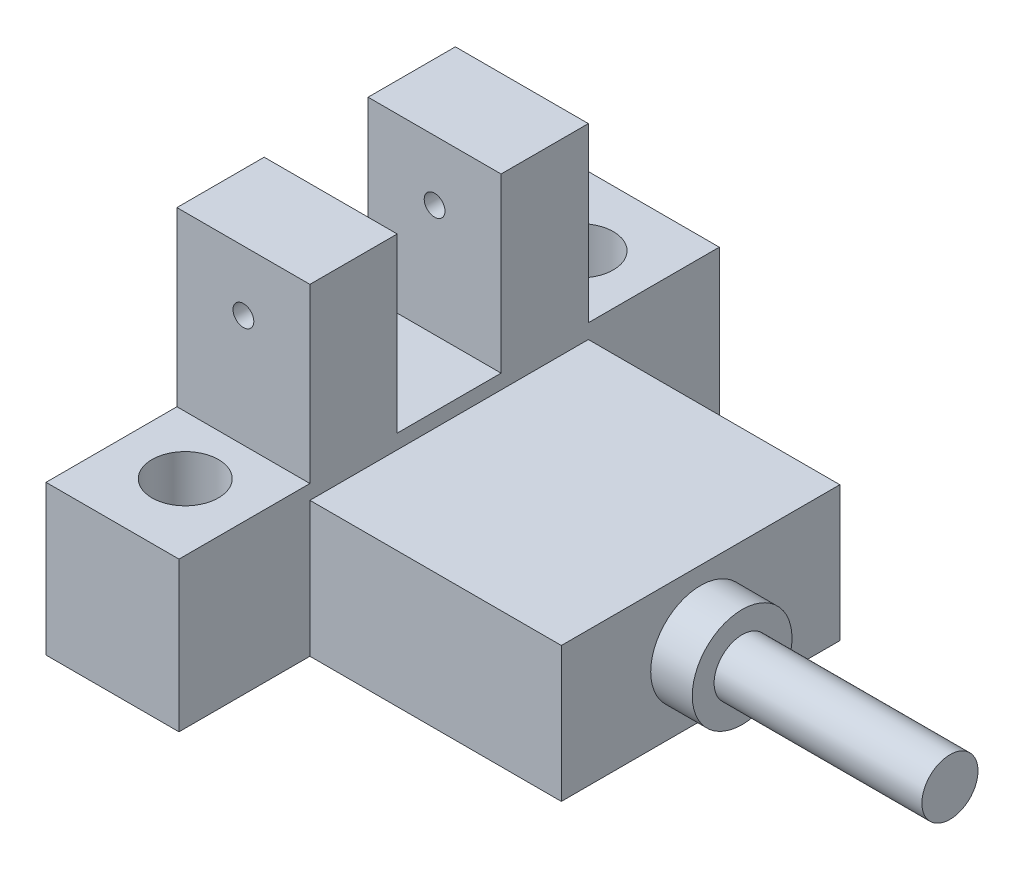
SolidWorks part; units mm, degrees
ref_plane "Ebene vorne" through (0, 0, 0) normal (0, 0, 1) x (1, 0, 0)
ref_plane "Ebene oben" through (0, 0, 0) normal (0, 1, 0) x (1, 0, 0)
ref_plane "Ebene rechts" through (0, 0, 0) normal (1, 0, 0) x (0, 0, -1)
sketch "Skizze1" plane through (0, 0, 0) normal (0, 0, 1) x (1, 0, 0)
  line L0 (0, 0) -> (0, 15.5)
  line L1 (0, 15.5) -> (6.4, 15.5)
  line L2 (6.4, 15.5) -> (6.4, 6.5)
  line L3 (6.4, 6.5) -> (18.5, 6.5)
  line L4 (18.5, 6.5) -> (18.5, 0)
  line L5 (18.5, 0) -> (0, 0)
  dimension "D1" = 6.5
  dimension "D2" = 6.4
  dimension "D3" = 18.5
  dimension "D4" = 15.5
extrude "Aufsatz-Linear austragen1" add sketch "Skizze1" along normal blind 26
sketch "Skizze2" plane through (0, 6.5, 0) normal (0, 1, 0) x (1, 0, 0)
  line L0 (6.4, -26) -> (6.4, 0) construction
  line L1 (6.4, -19.7) -> (18.5, -19.7)
  line L2 (6.4, -19.7) -> (6.4, -26)
  line L3 (6.4, -26) -> (18.5, -26)
  line L4 (18.5, -19.7) -> (18.5, -26)
  line L5 (18.5, -26) -> (18.5, 0) construction
  line L6 (6.4, 0) -> (18.5, 0)
  line L7 (6.4, 0) -> (6.4, -6.3)
  line L8 (6.4, -6.3) -> (18.5, -6.3)
  line L9 (18.5, 0) -> (18.5, -6.3)
  point P14 (18.5, -13)
  dimension "D1" = 13.4
  dimension "D2" = 6.7
extrude "Schnitt-Linear austragen1" cut sketch "Skizze2" against normal blind 26
sketch "Skizze3" plane through (0, 15.5, 0) normal (0, 1, 0) x (1, 0, 0)
  line L0 (6.4, -26) -> (6.4, 0) construction
  line L1 (0, -26) -> (6.4, -26)
  line L2 (0, -26) -> (0, -19.7)
  line L3 (0, -19.7) -> (6.4, -19.7)
  line L4 (6.4, -26) -> (6.4, -19.7)
  line L5 (18.5, -19.7) -> (6.4, -19.7) construction
  line L6 (0, 0) -> (6.4, 0)
  line L7 (0, 0) -> (0, -6.3)
  line L8 (0, -6.3) -> (6.4, -6.3)
  line L9 (6.4, 0) -> (6.4, -6.3)
  line L10 (6.4, -6.3) -> (18.5, -6.3) construction
extrude "Schnitt-Linear austragen2" cut sketch "Skizze3" against normal blind 8.3
sketch "Skizze4" plane through (0, 15.5, 0) normal (0, 1, 0) x (1, 0, 0)
  line L0 (0, -19.7) -> (0, -6.3) construction
  line L1 (0, -10.5) -> (6.4, -10.5)
  line L2 (0, -10.5) -> (0, -15.5)
  line L3 (0, -15.5) -> (6.4, -15.5)
  line L4 (6.4, -10.5) -> (6.4, -15.5)
  line L5 (6.4, -19.7) -> (6.4, -6.3) construction
  line L6 (0, -6.3) -> (6.4, -6.3) construction
  dimension "D1" = 5
  dimension "D2" = 4.2
extrude "Schnitt-Linear austragen3" cut sketch "Skizze4" against normal up to surface (8.3 mm away) up to face at (3.2, 7.2, 22.85)
sketch "Skizze5" plane through (0, 0, 19.7) normal (0, 0, 1) x (1, 0, 0)
  line L0 (6.4, 15.5) -> (0, 15.5) construction
  circle A0 centre (3.2, 12.6) radius 0.5
  dimension "D1" = 1
  dimension "D2" = 2.9
extrude "Schnitt-Linear austragen4" cut sketch "Skizze5" against normal through all
sketch "Skizze6" plane through (0, 7.2, 0) normal (0, 1, 0) x (1, 0, 0)
  line L0 (0, -10.5) -> (0, -15.5) construction
  line L1 (0, 0) -> (0, -6.3) construction
  circle A0 centre (3.2, -22.5) radius 1.6
  circle A1 centre (3.2, -3.5) radius 1.6
  point P4 (0, -13)
  dimension "D1" = 3.2
  dimension "D2" = 19
  dimension "D3" = 9.5
  dimension "D4" = 3.2
extrude "Schnitt-Linear austragen5" cut sketch "Skizze6" against normal blind 8.3
sketch "Skizze7" plane through (18.5, 0, 0) normal (1, 0, 0) x (0, 0, -1)
  circle A0 centre (-13, 3.25) radius 2.4
  dimension "D1" = 4.8
extrude "Aufsatz-Linear austragen2" add sketch "Skizze7" along normal blind 2
sketch "Skizze8" plane through (20.5, 0, 0) normal (1, 0, 0) x (0, 0, -1)
  circle A0 centre (-13, 3.25) radius 1.35
  dimension "D1" = 2.7
extrude "Aufsatz-Linear austragen3" add sketch "Skizze8" along normal blind 10
